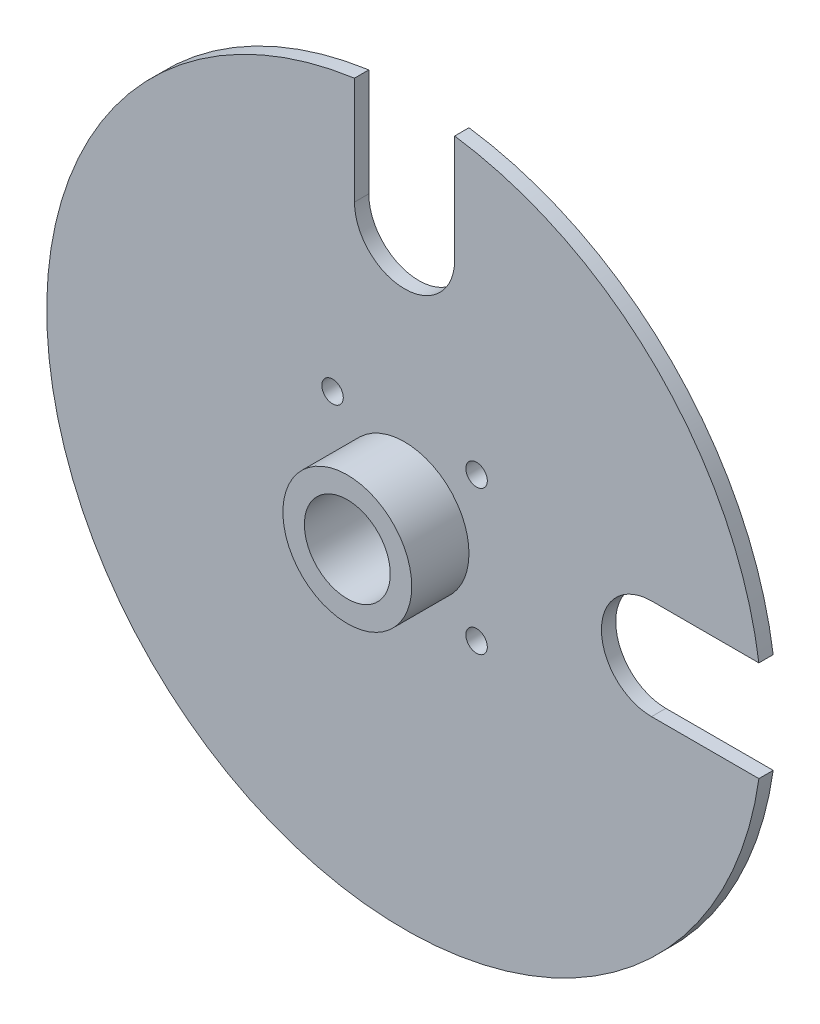
SolidWorks part; units mm, degrees
ref_plane "Front Plane" through (0, 0, 0) normal (0, 0, 1) x (1, 0, 0)
ref_plane "Top Plane" through (0, 0, 0) normal (0, 1, 0) x (1, 0, 0)
ref_plane "Right Plane" through (0, 0, 0) normal (1, 0, 0) x (0, 0, -1)
sketch "Sketch1" plane through (0, 0, 0) normal (0, 0, 1) x (1, 0, 0)
  line L0 (0, 0) -> (0, 22.0431) construction
  line L1 (0, 22.0431) -> (0, -27.0486) construction
  line L2 (0, -27.0486) -> (0, -2.5028) construction
  line L3 (0, 0) -> (34.3402, 0) construction
  line L4 (34.3402, 0) -> (-48.5021, 0) construction
  line L5 (0, 0) -> (-22.0431, 22.0431) construction
  circle A0 centre (0, 0) radius 6
  circle A1 centre (0, 0) radius 20
  circle A2 centre (-10.062, 10.062) radius 1.5
  circle A3 centre (10.062, 10.062) radius 1.5
  circle A4 centre (10.062, -10.062) radius 1.5
  circle A5 centre (-10.062, -10.062) radius 1.5
  dimension "D1" = 12
  dimension "D2" = 40
  dimension "D3" = 3
extrude "Boss-Extrude1" add sketch "Sketch1" along normal blind 5
sketch "Sketch2" plane through (0, 0, 5) normal (0, 0, 1) x (1, 0, 0)
  circle A0 centre (0, 0) radius 9
  circle A1 centre (0, 0) radius 6
  dimension "D2" = 12
  dimension "D1" = 3
extrude "Boss-Extrude2" add sketch "Sketch2" along normal blind 10
sketch "Sketch3" plane through (0, 0, 5) normal (0, 0, 1) x (1, 0, 0)
  circle A0 centre (0, 0) radius 50
  circle A1 centre (0, 0) radius 6
  dimension "D1" = 100
  dimension "D2" = 12
extrude "Boss-Extrude3" add sketch "Sketch3" along normal blind 2
sketch "Sketch4" plane through (0, 0, 7) normal (0, 0, 1) x (1, 0, 0)
  line L0 (0, 0) -> (0, 27.5076) construction
  line L1 (-7, 49.5076) -> (-7, 34.5076)
  line L2 (49.5076, -7) -> (34.5076, -7)
  line L3 (7, 49.5076) -> (7, 34.5076)
  line L4 (0, 49.5076) -> (0, 50) construction
  line L5 (49.5076, 7) -> (34.5076, 7)
  circle A0 centre (0, 0) radius 50 construction
  arc A1 (7, 49.5076) -> (-7, 49.5076) centre (0, 0) ccw
  arc A2 (-7, 34.5076) -> (7, 34.5076) centre (0, 34.5076) ccw
  arc A3 (34.5076, 7) -> (34.5076, -7) centre (34.5076, 0) ccw
  arc A4 (49.5076, -7) -> (49.5076, 7) centre (0, 0) ccw
  point P11 (0, 34.5076)
  point P21 (0, 0)
  point P42 (0, 0)
  dimension "D1" = 7
  dimension "D2" = 15
  dimension "D3" = 2
extrude "Cut-Extrude1" cut sketch "Sketch4" against normal blind 2
sketch "Sketch5" plane through (0, 0, 0) normal (0, 0, -1) x (-1, 0, 0)
  circle A0 centre (-10.062, 10.062) radius 1.5
  circle A1 centre (-10.062, -10.062) radius 1.5
  circle A2 centre (10.062, 10.062) radius 1.5
  circle A3 centre (10.062, -10.062) radius 1.5
extrude "Cut-Extrude2" cut sketch "Sketch5" against normal through all both and the other way through all
